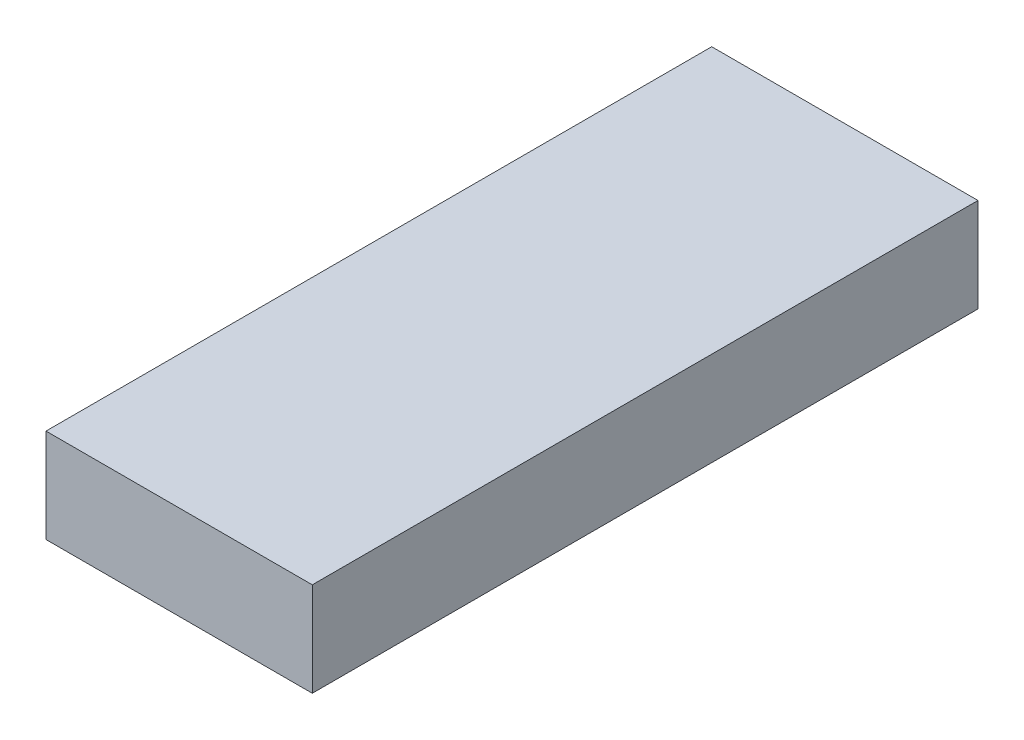
SolidWorks part; units mm, degrees
ref_plane "Front Plane" through (0, 0, 0) normal (0, 0, 1) x (1, 0, 0)
ref_plane "Top Plane" through (0, 0, 0) normal (0, 1, 0) x (1, 0, 0)
ref_plane "Right Plane" through (0, 0, 0) normal (1, 0, 0) x (0, 0, -1)
sketch "Sketch1" plane through (0, 0, 0) normal (0, 1, 0) x (1, 0, 0)
  line L1 (9, 22.5) -> (-9, 22.5)
  line L2 (9, 22.5) -> (9, -22.5)
  line L3 (9, -22.5) -> (-9, -22.5)
  line L4 (-9, 22.5) -> (-9, -22.5)
  line L5 (9, 22.5) -> (-9, -22.5) construction
  line L6 (9, -22.5) -> (-9, 22.5) construction
  point P0 (0, 0)
  dimension "D1" = 18
  dimension "D2" = 45
extrude "Boss-Extrude1" add sketch "Sketch1" along normal blind 6.35
